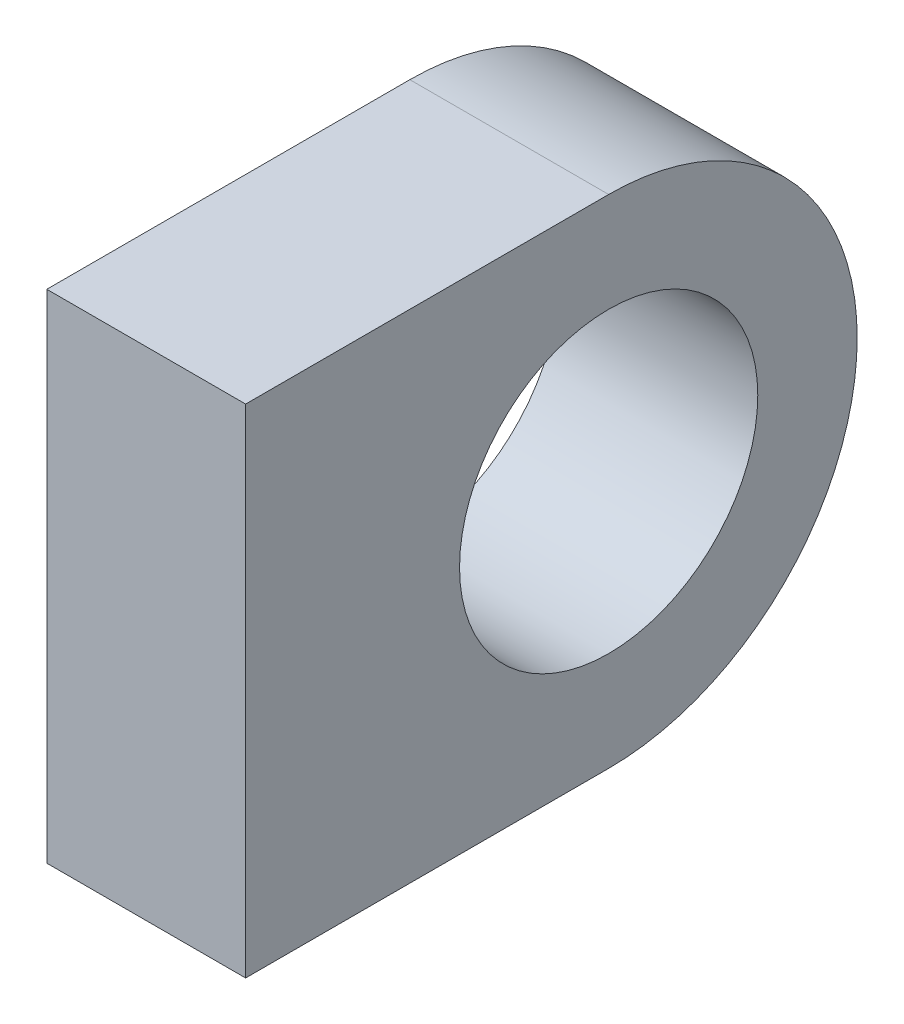
SolidWorks part; units mm, degrees
ref_plane "Front Plane" through (0, 0, 0) normal (0, 0, 1) x (1, 0, 0)
ref_plane "Top Plane" through (0, 0, 0) normal (0, 1, 0) x (1, 0, 0)
ref_plane "Right Plane" through (0, 0, 0) normal (1, 0, 0) x (0, 0, -1)
sketch "Sketch1" plane through (0, 0, 0) normal (1, 0, 0) x (0, 0, -1)
  line L0 (0, 12.5) -> (-18.2591, 12.5)
  line L1 (0, -12.5) -> (-18.2591, -12.5)
  line L2 (-18.2591, -12.5) -> (-18.2591, 12.5)
  circle A0 centre (0, 0) radius 7.5
  arc A1 (0, -12.5) -> (0, 12.5) centre (0, 0) ccw
  circle A2 centre (0, 0) radius 12.5 construction
  dimension "D1" = 15
  dimension "D3" = 18.2591
  dimension "D2" = 5
extrude "Boss-Extrude1" add sketch "Sketch1" along normal blind 10
